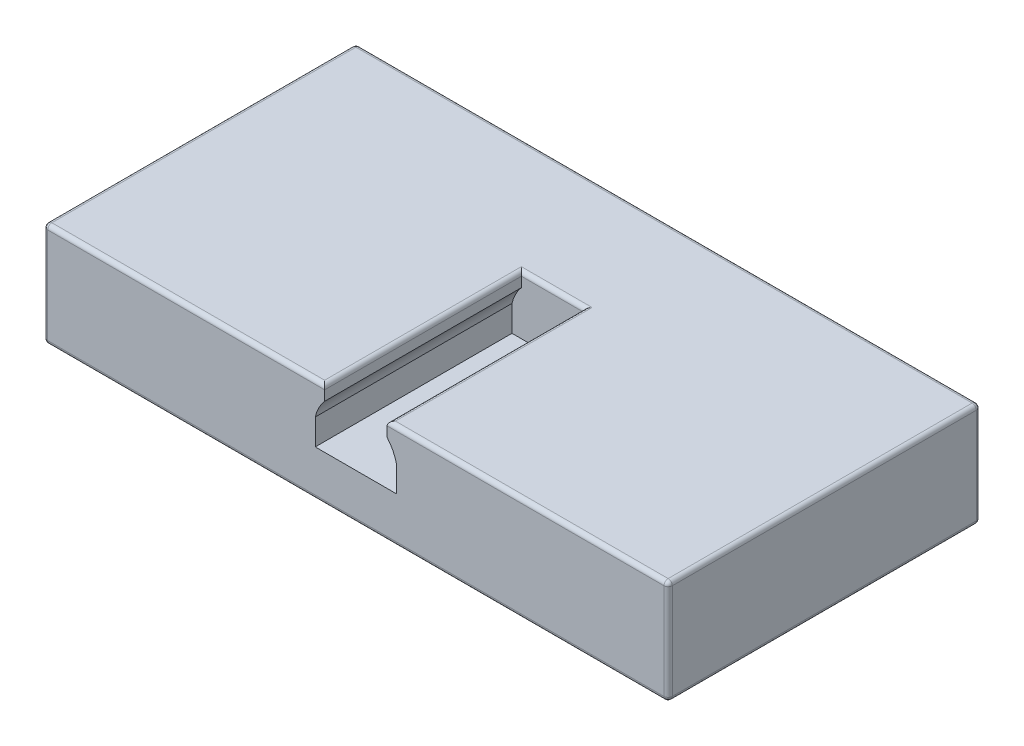
SolidWorks part; units mm, degrees
ref_plane "前视基准面" through (0, 0, 0) normal (0, 0, 1) x (1, 0, 0)
ref_plane "上视基准面" through (0, 0, 0) normal (0, 1, 0) x (1, 0, 0)
ref_plane "右视基准面" through (0, 0, 0) normal (1, 0, 0) x (0, 0, -1)
sketch "草图1" plane through (0, 0, 0) normal (0, 1, 0) x (1, 0, 0)
  line L1 (-15, 0) -> (15, 0)
  line L2 (-15, 0) -> (-15, 15)
  line L3 (-15, 15) -> (15, 15)
  line L4 (15, 0) -> (15, 15)
extrude "凸台-拉伸1" add sketch "草图1" along normal blind 5
sketch "草图2" plane through (0, 0, 0) normal (0, 0, 1) x (1, 0, 0)
  line L0 (-1.5, 5) -> (-1.5, 4.3229)
  line L1 (-15, 5) -> (15, 5) construction
  line L2 (1.5, 5) -> (1.5, 4.3229)
  line L3 (-1.95, 2.2) -> (1.95, 2.2)
  line L4 (-1.95, 2.2) -> (-1.95, 3.4444)
  line L5 (1.95, 3.4444) -> (1.95, 2.2)
  line L6 (-1.5, 5) -> (1.5, 5)
  arc A0 (-1.5, 4.3229) -> (-1.95, 3.4444) centre (0, 3) ccw
  arc A1 (1.95, 3.4444) -> (1.5, 4.3229) centre (0, 3) ccw
extrude "切除-拉伸1" cut sketch "草图2" against normal blind 9.45
sketch "草图3" plane through (0, 0, -15) normal (0, 0, -1) x (-1, 0, 0)
  line L0 (-9, 0) -> (-9, 0.6771)
  line L1 (-15, 0) -> (15, 0) construction
  line L2 (-6, 0) -> (-6, 0.6771)
  line L3 (-9.45, 2.8) -> (-5.55, 2.8)
  line L4 (-9.45, 2.8) -> (-9.45, 1.5556)
  line L5 (-5.55, 2.8) -> (-5.55, 1.5556)
  line L6 (-9, 0) -> (-6, 0)
  line L7 (0, 5.756) -> (0, -1.0178) construction
  line L8 (9, 0) -> (6, 0)
  line L9 (5.55, 2.8) -> (5.55, 1.5556)
  line L10 (9.45, 2.8) -> (9.45, 1.5556)
  line L11 (9.45, 2.8) -> (5.55, 2.8)
  line L12 (6, 0) -> (6, 0.6771)
  line L13 (9, 0) -> (9, 0.6771)
  arc A0 (-6, 0.6771) -> (-5.55, 1.5556) centre (-7.5, 2) ccw
  arc A1 (-9.45, 1.5556) -> (-9, 0.6771) centre (-7.5, 2) ccw
  arc A2 (9.45, 1.5556) -> (9, 0.6771) centre (7.5, 2) cw
  arc A3 (6, 0.6771) -> (5.55, 1.5556) centre (7.5, 2) cw
extrude "切除-拉伸2" cut sketch "草图3" against normal blind 9.45
fillet "圆角1" radius 0.2 24 edges at (-15, 0, -7.5) (-12, 0, -15) (12, 0, -15) (0, 0, -15) (0, 0, 0) (15, 0, -7.5) (0, 5, -15) (15, 5, -7.5) (8.25, 5, 0) (-8.25, 5, 0) (-15, 5, -7.5) (9, 0, -10.275) (7.5, 0, -5.55) (6, 0, -10.275) (-6, 0, -10.275) (-7.5, 0, -5.55) (-9, 0, -10.275) (1.5, 5, -4.725) (0, 5, -9.45) (-1.5, 5, -4.725) (-15, 2.5, -15) (-15, 2.5, 0) (15, 2.5, 0) (15, 2.5, -15)
